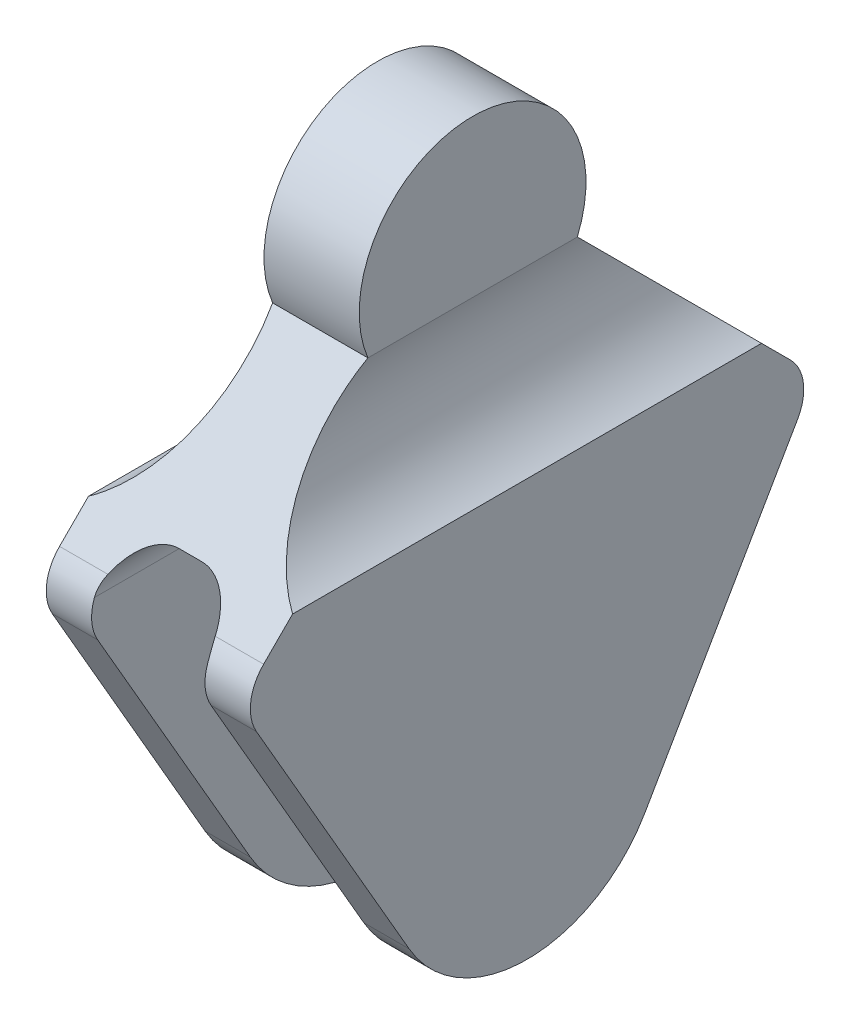
SolidWorks part; units mm, degrees
ref_plane "Front Plane" through (0, 0, 0) normal (0, 0, 1) x (1, 0, 0)
ref_plane "Top Plane" through (0, 0, 0) normal (0, 1, 0) x (1, 0, 0)
ref_plane "Right Plane" through (0, 0, 0) normal (1, 0, 0) x (0, 0, -1)
sketch "Sketch1" plane through (0, 0, 0) normal (1, 0, 0) x (0, 0, -1)
  line L0 (0, -1000) -> (0, 49000) construction
  line L1 (-1000, 0) -> (49000, 0) construction
  line L2 (-25.9808, -115) -> (-59.6719, -56.6452)
  line L3 (-58.0827, -44.5742) -> (-23.0907, -9.5822)
  line L4 (58.0827, -44.5742) -> (23.0907, -9.5822)
  line L9 (25.9808, -115) -> (59.6719, -56.6452)
  line L10 (51.5085, -38) -> (-51.5085, -38)
  arc A0 (23.0907, -9.5822) -> (-23.0907, -9.5822) centre (0, 0) ccw
  arc A1 (25.9808, -115) -> (-25.9808, -115) centre (0, -100) cw
  arc A2 (-59.6719, -56.6452) -> (-58.0827, -44.5742) centre (-51.0116, -51.6452) cw
  arc A3 (59.6719, -56.6452) -> (58.0827, -44.5742) centre (51.0116, -51.6452) ccw
  point P14 (-63.5085, -50)
  point P19 (0, -130)
  point P22 (0, 0)
  dimension "D4" = 50
  dimension "D1" = 25
  dimension "D2" = 30
  dimension "D5" = 10
  dimension "D3" = 100
  dimension "D6" = 90
  dimension "D7" = 60
  dimension "D9" = 92
extrude "Boss-Extrude2" add sketch "Sketch1" against normal blind 45 contours L9 A3 L4 L10 L3 A2 L2 A1 | L4 A0 L3 L10
sketch "Sketch3" plane through (0, 0, 0) normal (1, 0, 0) x (0, 0, -1)
  line L0 (-23.0907, -9.5822) -> (23.0907, -9.5822)
  arc A0 (-23.0907, -9.5822) -> (23.0907, -9.5822) centre (0, 0) cw
extrude "Cut-Extrude2" cut sketch "Sketch3" against normal blind 12
sketch "Sketch4" plane through (0, 0, 0) normal (1, 0, 0) x (0, 0, -1)
  line L1 (-23.0907, -9.5822) -> (23.0907, -9.5822)
  arc A1 (23.0907, -9.5822) -> (-23.0907, -9.5822) centre (0, 0) ccw
extrude "Cut-Extrude4" cut sketch "Sketch4" along normal blind 12 from surface at -45 starting at face at (-45, -53.9352, 0)
sketch "Sketch5" plane through (0, 0, 0) normal (1, 0, 0) x (0, 0, -1)
  line L0 (-51.5085, -38) -> (51.5085, -38)
  line L1 (58.0827, -44.5742) -> (23.0907, -9.5822) construction
  line L2 (51.5085, -38) -> (23.0907, -9.5822)
  line L3 (-58.0827, -44.5742) -> (-23.0907, -9.5822) construction
  line L4 (58.0827, -44.5742) -> (23.0907, -9.5822) construction
  line L5 (23.0907, -9.5822) -> (-23.0907, -9.5822)
  line L6 (-23.0907, -9.5822) -> (-51.5085, -38)
  line L7 (-51.5085, -38) -> (-23.0907, -9.5822)
  arc A1 (-25.9808, -115) -> (25.9808, -115) centre (0, -100) ccw construction
  point P6 (0, -130)
  point P7 (46.6437, -33.1352)
  dimension "D1" = 92
ref_plane "Plane2" through (0, -44.5742, 0) normal (0, -1, 0) x (-1, 0, 0)
sketch "Sketch9" plane through (0, 0, 0) normal (1, 0, 0) x (0, 0, -1)
  line L0 (-58.0827, -44.5742) -> (-58.0827, 34.1044) construction
ref_plane "Plane3" through (0, 0, 58.0827) normal (0, 0, 1) x (1, 0, 0)
sketch "Sketch10" plane through (0, 0, 0) normal (1, 0, 0) x (0, 0, -1)
  point P0 (-51.5085, -38)
sketch "Sketch11" plane through (0, 0, 58.0827) normal (0, 0, 1) x (1, 0, 0)
  line L0 (0, -44.5742) -> (0, 34.1044) construction
  line L1 (-12, -9.5822) -> (0, -9.5822)
  line L2 (0, -9.5822) -> (0, -38.1927)
  line L3 (-45, -44.5742) -> (-45, -9.5822) construction
  line L4 (-45, -9.5822) -> (-33, -9.5822)
  line L5 (-45, -38.1927) -> (-45, -9.5822)
  arc A0 (-12, -9.5822) -> (0, -38.1927) centre (12.0792, -16.3046) ccw
  arc A1 (-33, -9.5822) -> (-45, -38.1927) centre (-57.0792, -16.3046) cw
  dimension "D1" = 25
  dimension "D2" = 25
extrude "Cut-Extrude5" cut sketch "Sketch11" against normal through all
sketch "Sketch12" plane through (0, 0, 58.0827) normal (0, 0, 1) x (1, 0, 0)
  line L0 (-22.5, -1044.5742) -> (-22.5, 48955.4258) construction
  line L1 (-45, -44.5742) -> (0, -44.5742) construction
  line L2 (0, -38.1927) -> (-45, -38.1927) construction
  line L4 (-35, -130.1927) -> (-10, -130.1927)
  line L5 (-35, -130.1927) -> (-35, -48.1927)
  line L6 (-25, -38.1927) -> (-20, -38.1927)
  line L7 (-10, -130.1927) -> (-10, -48.1927)
  arc A0 (-35, -48.1927) -> (-25, -38.1927) centre (-25, -48.1927) cw
  arc A1 (-20, -38.1927) -> (-10, -48.1927) centre (-20, -48.1927) cw
  point P5 (-22.5, -44.5742)
  point P13 (0, 0)
  point P14 (-22.5, -130.1927)
  point P17 (-35, -38.1927)
  point P20 (-10, -38.1927)
  dimension "D3" = 10
  dimension "D1" = 25
  dimension "D2" = 92
extrude "Cut-Extrude7" cut sketch "Sketch12" against normal through all both and the other way through all
sketch "Sketch13" plane through (0, 0, 0) normal (1, 0, 0) x (0, 0, -1)
  line L0 (0, -1000) -> (0, 49000) construction
  line L1 (-1000, 0) -> (49000, 0) construction
sketch "Sketch14" plane through (-12, 0, 0) normal (1, 0, 0) x (0, 0, -1)
  line L0 (0, 25) -> (0, -9.4721) construction
  arc A0 (23.0907, -9.5822) -> (-23.0907, -9.5822) centre (0, 0) ccw construction
